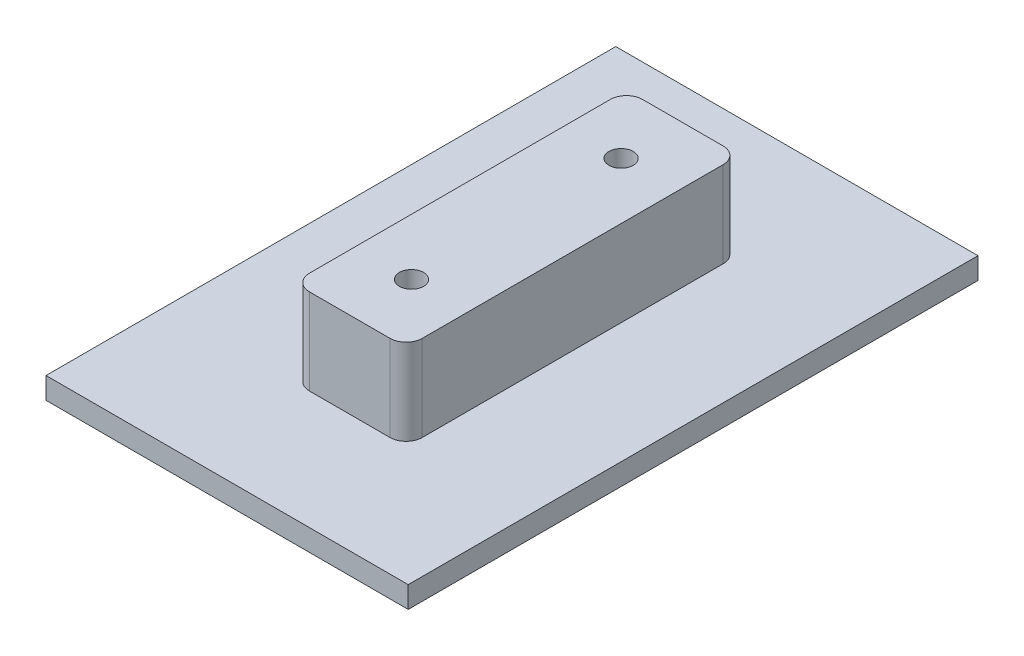
SolidWorks part; units mm, degrees
material "Alloy Steel"
ref_plane "Front Plane" through (0, 0, 0) normal (0, 0, 1) x (1, 0, 0)
ref_plane "Top Plane" through (0, 0, 0) normal (0, 1, 0) x (1, 0, 0)
ref_plane "Right Plane" through (0, 0, 0) normal (1, 0, 0) x (0, 0, -1)
other "Configuration Table"
sketch "Sketch1" plane through (0, 0, 0) normal (0, 1, 0) x (1, 0, 0)
  line L0 (-107.0007, 168.3199) -> (107.0007, -168.3199) construction
  line L1 (-107.0007, 168.3199) -> (107.0007, 168.3199)
  line L2 (-107.0007, 168.3199) -> (-107.0007, -168.3199)
  line L3 (-107.0007, -168.3199) -> (107.0007, -168.3199)
  line L4 (107.0007, 168.3199) -> (107.0007, -168.3199)
extrude "Extrude1" add sketch "Sketch1" against normal blind 12.7
sketch "Sketch2" plane through (0, 0, 0) normal (0, 1, 0) x (-1, 0, 0)
  line L32 (-35.8733, 88.9) -> (-35.8733, -88.9)
  line L33 (21.2767, 98.425) -> (-26.3483, 98.425)
  line L34 (30.8017, -88.9) -> (30.8017, 88.9)
  line L35 (-26.3483, -98.425) -> (21.2767, -98.425)
  line L36 (-35.8733, 88.9) -> (-35.8733, -88.9)
  line L37 (21.2767, 98.425) -> (-26.3483, 98.425)
  line L38 (30.8017, -88.9) -> (30.8017, 88.9)
  line L39 (-26.3483, -98.425) -> (21.2767, -98.425)
  circle A0 centre (-2.5358, 61.9125) radius 7.1438
  circle A1 centre (-2.5358, -61.9125) radius 7.1438
  arc A2 (4.608, -61.9125) -> (-9.6795, -61.9125) centre (-2.5358, -61.9125) ccw construction
  arc A3 (-9.6795, 61.9125) -> (4.608, 61.9125) centre (-2.5358, 61.9125) ccw construction
  arc A36 (-26.3483, 98.425) -> (-35.8733, 88.9) centre (-26.3483, 88.9) ccw
  arc A37 (30.8017, 88.9) -> (21.2767, 98.425) centre (21.2767, 88.9) ccw
  arc A38 (21.2767, -98.425) -> (30.8017, -88.9) centre (21.2767, -88.9) ccw
  arc A39 (-35.8733, -88.9) -> (-26.3483, -98.425) centre (-26.3483, -88.9) ccw
  arc A40 (-26.3483, 98.425) -> (-35.8733, 88.9) centre (-26.3483, 88.9) ccw
  arc A41 (30.8017, 88.9) -> (21.2767, 98.425) centre (21.2767, 88.9) ccw
  arc A42 (21.2767, -98.425) -> (30.8017, -88.9) centre (21.2767, -88.9) ccw
  arc A43 (-35.8733, -88.9) -> (-26.3483, -98.425) centre (-26.3483, -88.9) ccw
  dimension "D1" = 6.35
extrude "Extrude2" add sketch "Sketch2" along normal up to surface (50.7448 mm away)
